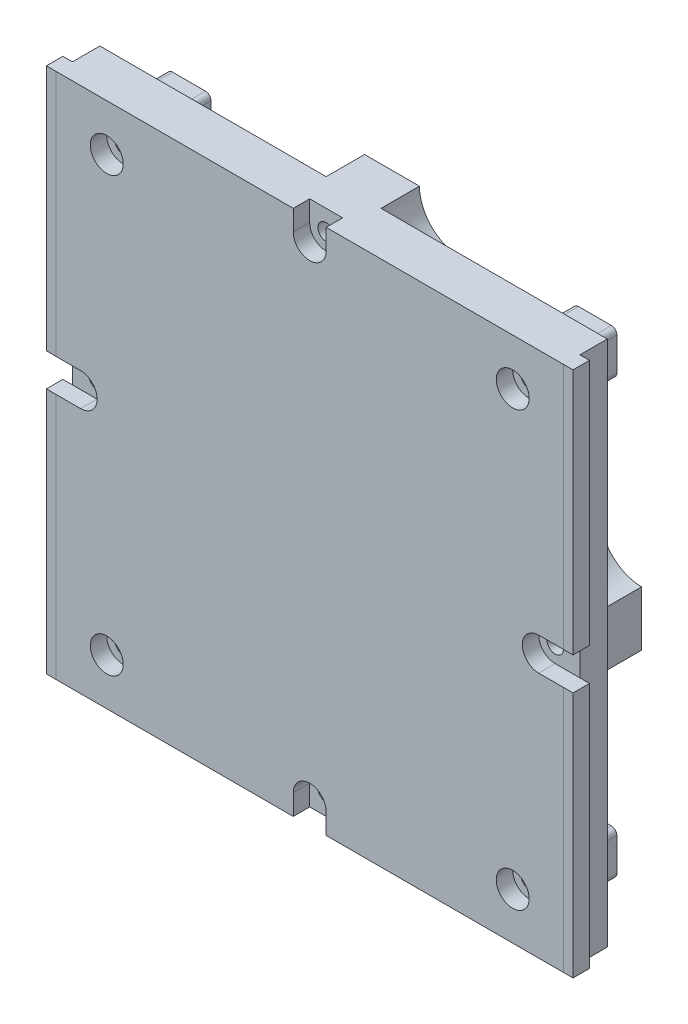
SolidWorks part; units mm, degrees
material "6061-T6 (SS)"
ref_plane "Front Plane" through (0, 0, 0) normal (0, 0, 1) x (1, 0, 0)
ref_plane "Top Plane" through (0, 0, 0) normal (0, 1, 0) x (1, 0, 0)
ref_plane "Right Plane" through (0, 0, 0) normal (1, 0, 0) x (0, 0, -1)
sketch "Sketch3" plane through (0, 48, 0) normal (0, 1, 0) x (1, 0, 0)
  line L0 (48, 27) -> (48, 30) construction
  line L1 (48, 0) -> (-48, 0)
  line L2 (48, 0) -> (48, -3)
  line L3 (48, -3) -> (-48, -3)
  line L4 (-48, 0) -> (-48, -3)
  line L5 (38, 0) -> (-38, 0) construction
  line L6 (-48, 27) -> (-48, 30) construction
extrude "Boss-Extrude1" add sketch "Sketch3" against normal up to surface (96 mm away)
sketch "Sketch4" plane through (0, 0, 0) normal (0, 0, -1) x (-1, 0, 0)
  line L0 (38, -12.5) -> (38, 12.5) construction
  line L1 (45.5, 5) -> (45.5, -5) construction
  line L2 (38, -12.5) -> (38, 12.5)
  line L3 (45.5, 5) -> (45.5, -5)
  line L4 (12.5, 40.5) -> (-12.5, 40.5) construction
  line L5 (-5, 48) -> (5, 48) construction
  line L6 (12.5, 40.5) -> (-12.5, 40.5)
  line L7 (-5, 48) -> (5, 48)
  line L8 (0, 0) -> (0, 57.3774) construction
  line L9 (0, 0) -> (62.4619, 0) construction
  line L10 (-5, -48) -> (5, -48)
  line L11 (12.5, -40.5) -> (-12.5, -40.5)
  line L12 (-45.5, 5) -> (-45.5, -5)
  line L13 (-38, -12.5) -> (-38, 12.5)
  arc A0 (45.5, -5) -> (38, -12.5) centre (45.5, -12.5) ccw construction
  arc A1 (38, 12.5) -> (45.5, 5) centre (45.5, 12.5) ccw construction
  arc A2 (45.5, -5) -> (38, -12.5) centre (45.5, -12.5) ccw
  arc A3 (38, 12.5) -> (45.5, 5) centre (45.5, 12.5) ccw
  arc A4 (-12.5, 40.5) -> (-5, 48) centre (-12.5, 48) ccw construction
  arc A5 (5, 48) -> (12.5, 40.5) centre (12.5, 48) ccw construction
  arc A6 (-12.5, 40.5) -> (-5, 48) centre (-12.5, 48) ccw
  arc A7 (5, 48) -> (12.5, 40.5) centre (12.5, 48) ccw
  circle A8 centre (0, 44.25) radius 1.5 construction
  circle A9 centre (41.75, 0) radius 1.5 construction
  circle A10 centre (0, 44.25) radius 1.5
  circle A11 centre (41.75, 0) radius 1.5
  arc A12 (-12.5, -40.5) -> (-5, -48) centre (-12.5, -48) cw
  arc A13 (5, -48) -> (12.5, -40.5) centre (12.5, -48) cw
  circle A14 centre (0, -44.25) radius 1.5
  arc A15 (-38, 12.5) -> (-45.5, 5) centre (-45.5, 12.5) cw
  circle A16 centre (-41.75, 0) radius 1.5
  arc A17 (-45.5, -5) -> (-38, -12.5) centre (-45.5, -12.5) cw
extrude "Boss-Extrude2" add sketch "Sketch4" along normal offset from surface (12 mm away) 10
sketch "Sketch5" plane through (0, 0, 0) normal (0, 0, -1) x (-1, 0, 0)
  line L0 (45.5, -5) -> (45.5, 5) construction
  line L1 (-40, 35.5) -> (-34, 35.5)
  line L2 (-41, 36.5) -> (-41, 42.5)
  line L3 (-40, 43.5) -> (-34, 43.5)
  line L4 (-33, 36.5) -> (-33, 42.5)
  line L5 (-41, 35.5) -> (-33, 43.5) construction
  line L6 (-41, 43.5) -> (-33, 35.5) construction
  line L7 (12.5, -40.5) -> (-12.5, -40.5) construction
  line L8 (0, 0) -> (-69.3927, 0) construction
  line L9 (0, 0) -> (0, 61.8676) construction
  line L10 (41, 43.5) -> (33, 35.5) construction
  line L11 (41, 35.5) -> (33, 43.5) construction
  line L12 (33, 36.5) -> (33, 42.5)
  line L13 (40, 43.5) -> (34, 43.5)
  line L14 (41, 36.5) -> (41, 42.5)
  line L15 (40, 35.5) -> (34, 35.5)
  line L16 (-41, -43.5) -> (-33, -35.5) construction
  line L17 (-41, -35.5) -> (-33, -43.5) construction
  line L18 (-33, -36.5) -> (-33, -42.5)
  line L19 (-40, -43.5) -> (-34, -43.5)
  line L20 (-41, -36.5) -> (-41, -42.5)
  line L21 (-40, -35.5) -> (-34, -35.5)
  line L22 (41, -35.5) -> (33, -43.5) construction
  line L23 (41, -43.5) -> (33, -35.5) construction
  line L24 (40, -35.5) -> (34, -35.5)
  line L25 (41, -36.5) -> (41, -42.5)
  line L26 (40, -43.5) -> (34, -43.5)
  line L27 (33, -36.5) -> (33, -42.5)
  arc A0 (-41, 42.5) -> (-40, 43.5) centre (-40, 42.5) cw
  arc A1 (-34, 35.5) -> (-33, 36.5) centre (-34, 36.5) ccw
  arc A2 (-40, 35.5) -> (-41, 36.5) centre (-40, 36.5) cw
  arc A3 (-34, 43.5) -> (-33, 42.5) centre (-34, 42.5) cw
  circle A4 centre (-37, 39.5) radius 1.5
  circle A5 centre (37, 39.5) radius 1.5
  arc A6 (34, 43.5) -> (33, 42.5) centre (34, 42.5) ccw
  arc A7 (40, 35.5) -> (41, 36.5) centre (40, 36.5) ccw
  arc A8 (34, 35.5) -> (33, 36.5) centre (34, 36.5) cw
  arc A9 (41, 42.5) -> (40, 43.5) centre (40, 42.5) ccw
  circle A10 centre (-37, -39.5) radius 1.5
  arc A11 (-34, -43.5) -> (-33, -42.5) centre (-34, -42.5) ccw
  arc A12 (-40, -35.5) -> (-41, -36.5) centre (-40, -36.5) ccw
  arc A13 (-34, -35.5) -> (-33, -36.5) centre (-34, -36.5) cw
  arc A14 (-41, -42.5) -> (-40, -43.5) centre (-40, -42.5) ccw
  arc A15 (41, -42.5) -> (40, -43.5) centre (40, -42.5) cw
  arc A16 (34, -35.5) -> (33, -36.5) centre (34, -36.5) ccw
  arc A17 (40, -35.5) -> (41, -36.5) centre (40, -36.5) cw
  arc A18 (34, -43.5) -> (33, -42.5) centre (34, -42.5) cw
  circle A19 centre (37, -39.5) radius 1.5
  point P0 (-37, 39.5)
  dimension "D1" = 1
  dimension "D3" = 3
  dimension "D2" = 8
  dimension "D4" = 43.5
  dimension "D5" = 41
extrude "Boss-Extrude3" add sketch "Sketch5" along normal up to surface (12 mm away) up to face at (41.75, 1.5, -12)
sketch "Sketch6" plane through (0, 0, 0) normal (0, 0, -1) x (-1, 0, 0)
  line L0 (-46.25, 48) -> (-46.25, -48)
  line L1 (-48, 48) -> (-5, 48) construction
  line L2 (-48, -48) -> (-5, -48) construction
  line L3 (46.25, 48) -> (46.25, -48)
  line L4 (5, 48) -> (48, 48) construction
  line L5 (5, -48) -> (48, -48) construction
  line L6 (48, -48) -> (48, 48) construction
  line L7 (-48, -48) -> (-48, 48) construction
  dimension "D1" = 1.75
  dimension "D2" = 1.75
split line "Split Line1"
sketch "Sketch7" plane through (0, 0, 3) normal (0, 0, 1) x (1, 0, 0)
  line L0 (-46.25, -48) -> (-46.25, 48) construction
  line L1 (46.25, -48) -> (46.25, 48) construction
  line L2 (-46.25, -48) -> (-46.25, 48)
  line L3 (46.25, -48) -> (46.25, 48)
split line "Split Line2"
sketch "Sketch8" plane through (0, 0, 0) normal (0, 0, -1) x (-1, 0, 0)
  line L1 (38, 40.5) -> (-38, 40.5)
  line L2 (38, 40.5) -> (38, -40.5)
  line L3 (38, -40.5) -> (-38, -40.5)
  line L4 (-38, 40.5) -> (-38, -40.5)
  line L5 (38, 40.5) -> (-38, -40.5) construction
  line L6 (38, -40.5) -> (-38, 40.5) construction
  line L8 (5, -48) -> (46.25, -48)
  line L9 (46.25, -48) -> (46.25, 48)
  line L10 (46.25, 48) -> (5, 48)
  line L11 (12.5, 40.5) -> (-12.5, 40.5)
  line L12 (-5, 48) -> (-46.25, 48)
  line L13 (-46.25, 48) -> (-46.25, -48)
  line L14 (-46.25, -48) -> (-5, -48)
  line L15 (-12.5, -40.5) -> (12.5, -40.5)
  line L16 (5, -48) -> (46.25, -48)
  line L17 (46.25, -48) -> (46.25, 48)
  line L18 (46.25, 48) -> (5, 48)
  line L19 (12.5, 40.5) -> (-12.5, 40.5)
  line L20 (-5, 48) -> (-46.25, 48)
  line L21 (-46.25, 48) -> (-46.25, -48)
  line L22 (-46.25, -48) -> (-5, -48)
  line L23 (-12.5, -40.5) -> (12.5, -40.5)
  arc A4 (5, 48) -> (12.5, 40.5) centre (12.5, 48) ccw
  arc A5 (-12.5, 40.5) -> (-5, 48) centre (-12.5, 48) ccw
  arc A6 (-5, -48) -> (-12.5, -40.5) centre (-12.5, -48) ccw
  arc A7 (12.5, -40.5) -> (5, -48) centre (12.5, -48) ccw
  arc A8 (5, 48) -> (12.5, 40.5) centre (12.5, 48) ccw
  arc A9 (-12.5, 40.5) -> (-5, 48) centre (-12.5, 48) ccw
  arc A10 (-5, -48) -> (-12.5, -40.5) centre (-12.5, -48) ccw
  arc A11 (12.5, -40.5) -> (5, -48) centre (12.5, -48) ccw
  point P2 (0, 0)
  dimension "D2" = 8.25
  dimension "D1" = 0
extrude "Boss-Extrude4" add sketch "Sketch8" along normal blind 5 contours L22 A10 L3 L4 L1 A9 L20 L21 | L3 A11 L16 L17 L18 A8 L1 L2
sketch "Sketch10" plane through (0, 0, 3) normal (0, 0, 1) x (1, 0, 0)
  circle A0 centre (37, -39.5) radius 1.5
  circle A1 centre (0, -44.25) radius 1.5
  circle A2 centre (-37, -39.5) radius 1.5
  circle A3 centre (-41.75, 0) radius 1.5
  circle A4 centre (-37, 39.5) radius 1.5
  circle A5 centre (0, 44.25) radius 1.5
  circle A6 centre (37, 39.5) radius 1.5
  circle A7 centre (41.75, 0) radius 1.5
  point P0 (37, 39.5)
  point P1 (0, 44.25)
  point P3 (-37, 39.5)
  point P5 (-41.75, 0)
  point P7 (-37, -39.5)
  point P9 (0, -44.25)
  point P11 (37, -39.5)
  point P13 (41.75, 0)
  dimension "D1" = 3
  dimension "D2" = 3
  dimension "D3" = 3
  dimension "D4" = 3
  dimension "D5" = 3
  dimension "D6" = 3
  dimension "D7" = 3
  dimension "D8" = 3
extrude "Cut-Extrude1" cut sketch "Sketch10" against normal through all
sketch "Sketch11" plane through (0, 0, 3) normal (0, 0, 1) x (1, 0, 0)
  line L0 (0, 0) -> (0, 75.5925) construction
  circle A0 centre (0, -44.25) radius 3
  circle A1 centre (-37, -39.5) radius 3
  circle A2 centre (-41.75, 0) radius 3
  circle A3 centre (-37, 39.5) radius 3
  circle A4 centre (0, 44.25) radius 3
  circle A5 centre (37, -39.5) radius 3
  circle A6 centre (41.75, 0) radius 3
  circle A7 centre (37, 39.5) radius 3
  dimension "D1" = 6
  dimension "D2" = 6
  dimension "D3" = 6
  dimension "D4" = 6
  dimension "D5" = 6
extrude "Cut-Extrude2" cut sketch "Sketch11" against normal blind 3
sketch "Sketch12" plane through (0, 0, 3) normal (0, 0, 1) x (1, 0, 0)
  line L0 (3, -44.25) -> (3, -51.0443)
  line L1 (3, -51.0443) -> (-3, -51.0443)
  line L2 (-3, -51.0443) -> (-3, -44.25)
  line L3 (0, 0) -> (65.4679, 0) construction
  line L4 (3, 44.25) -> (3, 51.0443)
  line L5 (-3, 51.0443) -> (-3, 44.25)
  line L6 (3, 51.0443) -> (-3, 51.0443)
  line L7 (41.75, -3) -> (50.1684, -3)
  line L8 (50.1684, -3) -> (50.1684, 3)
  line L9 (50.1684, 3) -> (41.75, 3)
  line L10 (0, 0) -> (0, 22.2056) construction
  line L11 (-50.1684, -3) -> (-50.1684, 3)
  line L12 (-50.1684, 3) -> (-41.75, 3)
  line L13 (-41.75, -3) -> (-50.1684, -3)
  circle A0 centre (0, -44.25) radius 3 construction
  arc A1 (-3, -44.25) -> (3, -44.25) centre (0, -44.25) ccw
  arc A2 (-3, 44.25) -> (3, 44.25) centre (0, 44.25) cw
  circle A3 centre (41.75, 0) radius 3 construction
  arc A4 (41.75, -3) -> (41.75, 3) centre (41.75, 0) ccw
  arc A5 (-41.75, -3) -> (-41.75, 3) centre (-41.75, 0) cw
  dimension "D1" = 6.7943
  dimension "D2" = 6
  dimension "D3" = 6
  dimension "D4" = 8.4184
extrude "Cut-Extrude3" cut sketch "Sketch12" against normal blind 3
